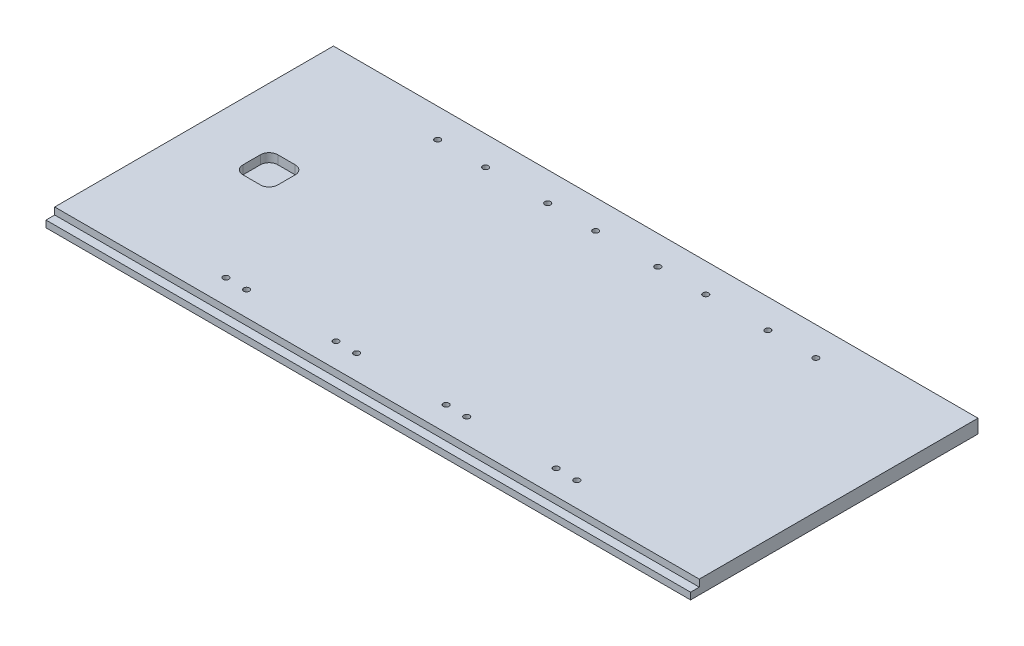
SolidWorks part; units mm, degrees
ref_plane "Front Plane" through (0, 0, 0) normal (0, 0, 1) x (1, 0, 0)
ref_plane "Top Plane" through (0, 0, 0) normal (0, 1, 0) x (1, 0, 0)
ref_plane "Right Plane" through (0, 0, 0) normal (1, 0, 0) x (0, 0, -1)
sketch "Sketch3" plane through (0, 0, 0) normal (0, 1, 0) x (1, 0, 0)
  line L1 (234.95, -104.775) -> (-234.95, -104.775)
  line L2 (234.95, -104.775) -> (234.95, 104.775)
  line L3 (234.95, 104.775) -> (-234.95, 104.775)
  line L4 (-234.95, -104.775) -> (-234.95, 104.775)
  line L5 (234.95, -104.775) -> (-234.95, 104.775) construction
  line L6 (234.95, 104.775) -> (-234.95, -104.775) construction
  point P0 (0, 0)
  dimension "D1" = 469.9
  dimension "D2" = 209.55
extrude "Boss-Extrude1" add sketch "Sketch3" along normal blind 10
sketch "Sketch4" plane through (0, 10, 0) normal (0, 1, 0) x (1, 0, 0)
  circle A6 centre (-102.9, 83.65) radius 2.1
  circle A8 centre (-22.65, 83.65) radius 2.1
  circle A11 centre (57.6, 83.65) radius 2.1
  circle A13 centre (137.85, 83.65) radius 2.1
  circle A14 centre (112.85, -80.65) radius 2.1
  circle A15 centre (32.6, -80.65) radius 2.1
  circle A16 centre (-47.65, -80.65) radius 2.1
  circle A17 centre (-127.9, -80.65) radius 2.1
  point P0 (-102.9, 83.65)
  point P1 (-22.65, 83.65)
  point P3 (57.6, 83.65)
  point P5 (137.85, 83.65)
  point P7 (-127.9, -80.65)
  point P9 (-47.65, -80.65)
  point P11 (32.6, -80.65)
  point P13 (112.85, -80.65)
  dimension "D1" = 4.2
extrude "Cut-Extrude3" cut sketch "Sketch4" against normal through all
thread "Thread1" pitch 0.8 start angle 0, offset 0, length 0, pitch 0.8, diameter 4.2
ref_plane "Plane3" through (-105, 12.7, -83.65) normal (0, 0, 1) x (-1, 0, 0)
sketch "Thread Profile3" plane through (-105, 12.7, -83.65) normal (0, 0, 1) x (-1, 0, 0)
  line L0 (0, 0) -> (0, 0.8) construction
  line L1 (0, 0) -> (0.433, 0.25)
  line L2 (0.433, 0.25) -> (0.433, 0.35)
  line L3 (0.433, 0.35) -> (0, 0.6)
  line L4 (0.433, 0.3) -> (0, 0.3) construction
  line L11 (0, 0) -> (0, 0.6)
  point P2 (0, 0)
  dimension "Pitch" = 0.8
  dimension "Profile_Angle" = 60
  dimension "Profile_Land" = 0.1
  dimension "Profile_Height" = 0.433
sketch "Sketch5" plane through (0, 10, 0) normal (0, 1, 0) x (1, 0, 0)
  circle A0 centre (-137.85, 83.65) radius 2.1
  circle A1 centre (-57.6, 83.65) radius 2.1
  circle A2 centre (22.65, 83.65) radius 2.1
  circle A3 centre (102.9, 83.65) radius 2.1
  circle A4 centre (-112.85, -80.65) radius 2.1
  circle A5 centre (-32.6, -80.65) radius 2.1
  circle A6 centre (47.65, -80.65) radius 2.1
  circle A7 centre (127.9, -80.65) radius 2.1
  point P0 (-137.85, 83.65)
  point P1 (-57.6, 83.65)
  point P3 (22.65, 83.65)
  point P5 (102.9, 83.65)
  point P7 (-112.85, -80.65)
  point P9 (-32.6, -80.65)
  point P11 (47.65, -80.65)
  point P13 (127.9, -80.65)
  dimension "D1" = 4.2
extrude "Cut-Extrude4" cut sketch "Sketch5" against normal through all
sketch "Sketch7" plane through (0, 10, 0) normal (0, 1, 0) x (1, 0, 0)
  line L0 (-234.95, -104.775) -> (234.95, -104.775) construction
  line L1 (-192.95, 15.875) -> (-167.55, 15.875)
  line L2 (-192.95, 15.875) -> (-192.95, -9.525)
  line L3 (-192.95, -9.525) -> (-167.55, -9.525)
  line L4 (-167.55, 15.875) -> (-167.55, -9.525)
  line L5 (-192.95, 15.875) -> (-167.55, -9.525) construction
  line L6 (-192.95, -9.525) -> (-167.55, 15.875) construction
  line L8 (-154.85, -86.65) -> (-154.85, 86.65) construction
  point P0 (-180.25, 3.175)
  dimension "D1" = 25.4
  dimension "D2" = 25.4
  dimension "D3" = 107.95
  dimension "D4" = 12.7
extrude "Cut-Extrude5" cut sketch "Sketch7" against normal blind 6.35
sketch "Sketch8" plane through (-234.95, 0, 0) normal (-1, 0, 0) x (0, 0, 1)
  line L1 (104.775, 10) -> (98.425, 10)
  line L2 (104.775, 10) -> (104.775, 4.92)
  line L3 (104.775, 4.92) -> (98.425, 4.92)
  line L4 (98.425, 10) -> (98.425, 4.92)
  dimension "D1" = 6.35
  dimension "D2" = 5.08
extrude "Cut-Extrude6" cut sketch "Sketch8" against normal up to next
fillet "Fillet1" radius 6.35 4 edges at (-167.55, 6.825, 9.525) (-192.95, 6.825, 9.525) (-192.95, 6.825, -15.875) (-167.55, 6.825, -15.875)
